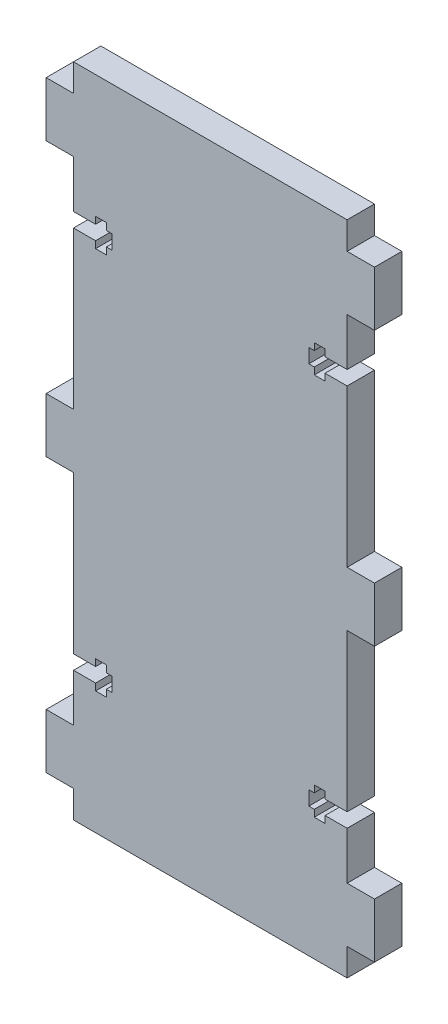
SolidWorks part; units mm, degrees
ref_plane "Front Plane" through (0, 0, 0) normal (0, 0, 1) x (1, 0, 0)
ref_plane "Top Plane" through (0, 0, 0) normal (0, 1, 0) x (1, 0, 0)
ref_plane "Right Plane" through (0, 0, 0) normal (1, 0, 0) x (0, 0, -1)
sketch "Sketch1" plane through (0, 0, 0) normal (0, 0, 1) x (1, 0, 0)
  line L1 (0, 0) -> (63.5, 0)
  line L2 (0, 0) -> (0, 152.4)
  line L3 (0, 152.4) -> (63.5, 152.4)
  line L4 (63.5, 0) -> (63.5, 152.4)
  dimension "D1" = 152.4
  dimension "D2" = 63.5
extrude "Boss-Extrude1" add sketch "Sketch1" along normal blind 6.35
sketch "Sketch2" plane through (0, 0, 6.35) normal (0, 0, 1) x (1, 0, 0)
  line L0 (0, 76.2) -> (63.5, 76.2) construction
  line L1 (0, 146.05) -> (-6.35, 146.05)
  line L2 (0, 146.05) -> (0, 133.35)
  line L3 (0, 133.35) -> (-6.35, 133.35)
  line L4 (-6.35, 146.05) -> (-6.35, 133.35)
  line L5 (0, 6.35) -> (-6.35, 6.35)
  line L6 (0, 6.35) -> (0, 19.05)
  line L7 (0, 19.05) -> (-6.35, 19.05)
  line L8 (-6.35, 6.35) -> (-6.35, 19.05)
  line L9 (0, 152.4) -> (0, 0) construction
  line L10 (63.5, 0) -> (63.5, 152.4) construction
  line L11 (-6.35, 76.2) -> (0, 76.2) construction
  line L12 (0, 82.55) -> (-6.35, 82.55)
  line L13 (0, 82.55) -> (0, 69.85)
  line L14 (0, 69.85) -> (-6.35, 69.85)
  line L15 (-6.35, 82.55) -> (-6.35, 69.85)
  line L16 (31.75, 152.4) -> (31.75, 0) construction
  line L17 (63.5, 152.4) -> (0, 152.4) construction
  line L18 (0, 0) -> (63.5, 0) construction
  line L19 (69.85, 146.05) -> (69.85, 133.35)
  line L20 (63.5, 133.35) -> (69.85, 133.35)
  line L21 (63.5, 146.05) -> (63.5, 133.35)
  line L22 (63.5, 146.05) -> (69.85, 146.05)
  line L23 (0, 82.55) -> (-6.35, 82.55)
  line L24 (0, 69.85) -> (-6.35, 69.85)
  line L25 (0, 82.55) -> (-6.35, 82.55)
  line L26 (0, 69.85) -> (-6.35, 69.85)
  line L27 (0, 82.55) -> (-6.35, 82.55)
  line L28 (0, 69.85) -> (-6.35, 69.85)
  line L29 (69.85, 6.35) -> (69.85, 19.05)
  line L30 (63.5, 19.05) -> (69.85, 19.05)
  line L31 (63.5, 6.35) -> (63.5, 19.05)
  line L32 (63.5, 6.35) -> (69.85, 6.35)
  line L33 (0, 82.55) -> (-6.35, 82.55)
  line L34 (0, 69.85) -> (-6.35, 69.85)
  line L35 (0, 82.55) -> (-6.35, 82.55)
  line L36 (0, 69.85) -> (-6.35, 69.85)
  line L37 (0, 82.55) -> (-6.35, 82.55)
  line L38 (0, 69.85) -> (-6.35, 69.85)
  line L39 (0, 82.55) -> (-6.35, 82.55)
  line L40 (0, 69.85) -> (-6.35, 69.85)
  line L41 (69.85, 76.2) -> (63.5, 76.2) construction
  line L42 (63.5, 69.85) -> (69.85, 69.85)
  line L43 (63.5, 82.55) -> (69.85, 82.55)
  line L44 (63.5, 69.85) -> (69.85, 69.85)
  line L45 (63.5, 82.55) -> (69.85, 82.55)
  line L46 (63.5, 69.85) -> (69.85, 69.85)
  line L47 (63.5, 82.55) -> (69.85, 82.55)
  line L48 (63.5, 69.85) -> (69.85, 69.85)
  line L49 (63.5, 82.55) -> (69.85, 82.55)
  line L50 (63.5, 69.85) -> (69.85, 69.85)
  line L51 (63.5, 82.55) -> (69.85, 82.55)
  line L52 (63.5, 69.85) -> (69.85, 69.85)
  line L53 (63.5, 82.55) -> (69.85, 82.55)
  line L54 (63.5, 69.85) -> (69.85, 69.85)
  line L55 (63.5, 82.55) -> (69.85, 82.55)
  line L56 (69.85, 82.55) -> (69.85, 69.85)
  line L57 (63.5, 69.85) -> (69.85, 69.85)
  line L58 (63.5, 82.55) -> (63.5, 69.85)
  line L59 (63.5, 82.55) -> (69.85, 82.55)
  line M1 (0, 152.4) -> (0, 0)
  line M3 (63.5, 0) -> (63.5, 152.4)
  dimension "D1" = 6.35
  dimension "D2" = 12.7
  dimension "D3" = 12.7
  dimension "D4" = 12.7
  dimension "D5" = 6.35
  dimension "D6" = 6.35
  dimension "D7" = 6.35
extrude "Boss-Extrude3" add sketch "Sketch2" against normal blind 6.35 contours L12 L15 L14 M1 | L22 L20 L19 M3 | L56 L43 L42 M3 | L32 L29 L30 M3 | L8 L5 L7 M1 | L4 L3 L2 L1
sketch "Sketch4" plane through (0, 0, 6.35) normal (0, 0, 1) x (1, 0, 0)
  line L0 (31.75, 152.4) -> (31.75, 0) construction
  line L1 (63.5, 152.4) -> (0, 152.4) construction
  line L2 (0, 0) -> (63.5, 0) construction
  line L3 (0, 133.35) -> (0, 82.55) construction
  line L4 (0, 122.301) -> (8.89, 122.301)
  line L5 (0, 122.301) -> (0, 118.999)
  line L6 (0, 118.999) -> (8.89, 118.999)
  line L7 (8.89, 122.301) -> (8.89, 118.999)
  line L8 (5.12, 120.65) -> (7.62, 120.65) construction
  line L9 (5.12, 123.9) -> (7.62, 123.9)
  line L10 (5.12, 123.9) -> (5.12, 117.4)
  line L11 (5.12, 117.4) -> (7.62, 117.4)
  line L12 (7.62, 123.9) -> (7.62, 117.4)
  line L13 (0, 120.65) -> (8.89, 120.65) construction
  line L14 (0, 133.35) -> (-6.35, 133.35) construction
  line L15 (-6.35, 76.2) -> (69.85, 76.2) construction
  line L16 (-6.35, 82.55) -> (-6.35, 69.85) construction
  line L17 (69.85, 82.55) -> (69.85, 69.85) construction
  line L18 (0, 31.75) -> (8.89, 31.75) construction
  line L19 (5.12, 31.75) -> (7.62, 31.75) construction
  line L20 (7.62, 28.5) -> (7.62, 35)
  line L21 (5.12, 35) -> (7.62, 35)
  line L22 (5.12, 28.5) -> (5.12, 35)
  line L23 (5.12, 28.5) -> (7.62, 28.5)
  line L24 (8.89, 30.099) -> (8.89, 33.401)
  line L25 (0, 33.401) -> (8.89, 33.401)
  line L26 (0, 30.099) -> (0, 33.401)
  line L27 (0, 30.099) -> (8.89, 30.099)
  line L28 (58.38, 31.75) -> (55.88, 31.75) construction
  line L29 (63.5, 31.75) -> (54.61, 31.75) construction
  line L30 (63.5, 120.65) -> (54.61, 120.65) construction
  line L31 (58.38, 120.65) -> (55.88, 120.65) construction
  line L32 (63.5, 30.099) -> (54.61, 30.099)
  line L33 (63.5, 30.099) -> (63.5, 33.401)
  line L34 (63.5, 33.401) -> (54.61, 33.401)
  line L35 (54.61, 30.099) -> (54.61, 33.401)
  line L36 (58.38, 28.5) -> (55.88, 28.5)
  line L37 (58.38, 28.5) -> (58.38, 35)
  line L38 (58.38, 35) -> (55.88, 35)
  line L39 (55.88, 28.5) -> (55.88, 35)
  line L40 (55.88, 123.9) -> (55.88, 117.4)
  line L41 (58.38, 117.4) -> (55.88, 117.4)
  line L42 (58.38, 123.9) -> (58.38, 117.4)
  line L43 (58.38, 123.9) -> (55.88, 123.9)
  line L44 (54.61, 122.301) -> (54.61, 118.999)
  line L45 (63.5, 118.999) -> (54.61, 118.999)
  line L46 (63.5, 122.301) -> (63.5, 118.999)
  line L47 (63.5, 122.301) -> (54.61, 122.301)
  dimension "D1" = 3.302
  dimension "D2" = 6.5
  dimension "D3" = 2.5
  dimension "D4" = 1.27
  dimension "D5" = 8.89
  dimension "D6" = 12.7
extrude "Cut-Extrude4" cut sketch "Sketch4" against normal blind 6.35 contours L6 L7 L4 L5 | L9 L12 L11 L10 | L21 L20 L23 L22 | L24 L25 L26 L27 | L35 L34 L33 L32 | L38 L39 L36 L37 | L41 L40 L43 L42 | L45 L44 L47 L46
